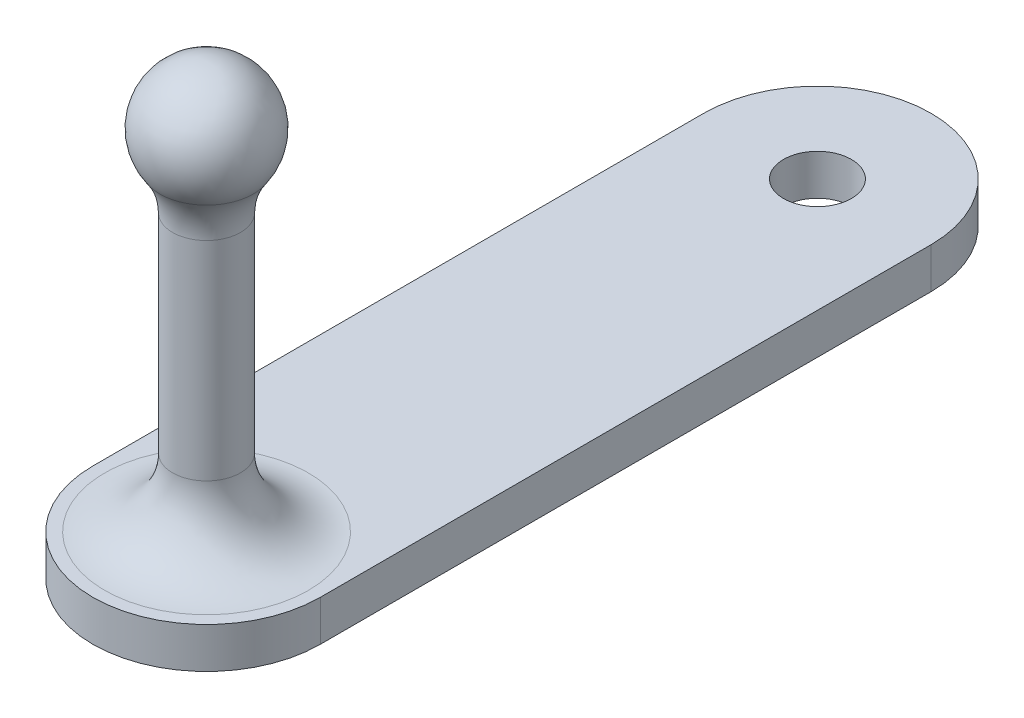
SolidWorks part; units mm, degrees
ref_plane "Front Plane" through (0, 0, 0) normal (0, 0, 1) x (1, 0, 0)
ref_plane "Top Plane" through (0, 0, 0) normal (0, 1, 0) x (1, 0, 0)
ref_plane "Right Plane" through (0, 0, 0) normal (1, 0, 0) x (0, 0, -1)
sketch "Sketch1" plane through (0, 0, 0) normal (0, 0, 1) x (1, 0, 0)
  line L0 (0, 4.25) -> (0, -25.75)
  line L1 (0, -25.75) -> (-2.5, -25.75)
  line L2 (-2.5, -25.75) -> (-2.5, -3.4369)
  arc A0 (0, 4.25) -> (-2.5, -3.4369) centre (0, 0) ccw
  dimension "D1" = 8.5
  dimension "D2" = 30
  dimension "D3" = 2.5
revolve "Revolve1" add sketch "Sketch1" angle 360 about L0
sketch "Sketch3" plane through (0, -25.75, 0) normal (0, -1, 0) x (-1, 0, 0)
  line L0 (0, 45) -> (0, 0) construction
  line L1 (8.3783, 45) -> (8.3783, 0)
  line L2 (-8.3783, 45) -> (-8.3783, 0)
  arc A0 (8.3783, 45) -> (-8.3783, 45) centre (0, 45) ccw
  arc A1 (-8.3783, 0) -> (8.3783, 0) centre (0, 0) ccw
  circle A2 centre (0, 45) radius 2.5
  point P2 (0, 22.5)
  dimension "D2" = 5
  dimension "D1" = 45
extrude "Boss-Extrude1" add sketch "Sketch3" along normal blind 3
fillet "Fillet1" radius 5 2 edges at (-2.5, -3.4369, 0) (-2.5, -25.75, 0)
